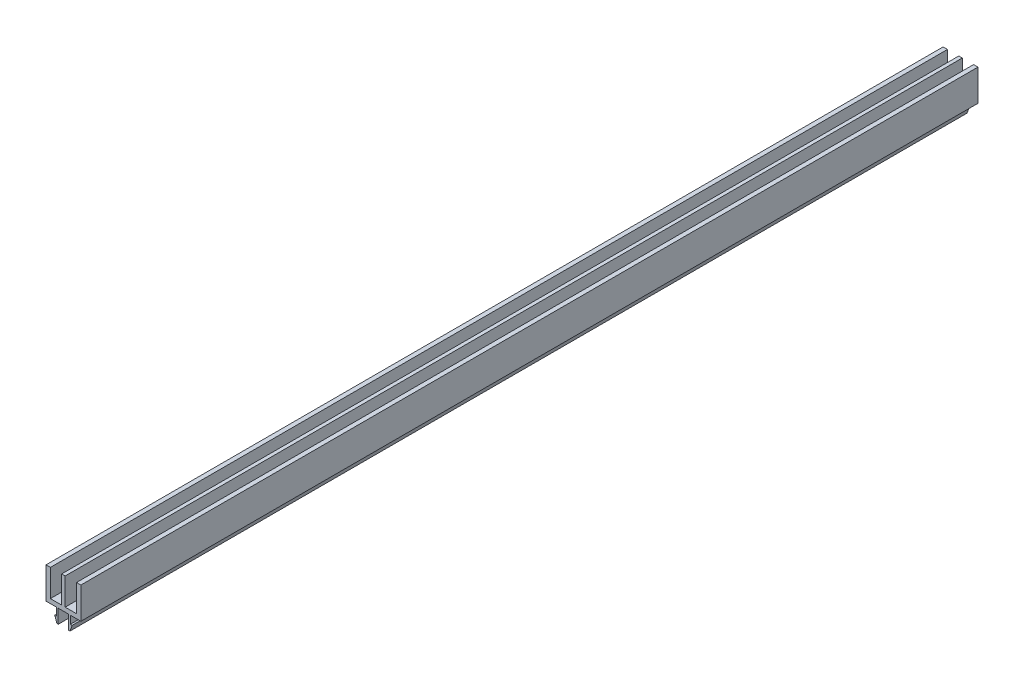
SolidWorks part; units mm, degrees
ref_plane "Plan de face" through (0, 0, 0) normal (0, 0, 1) x (1, 0, 0)
ref_plane "Plan de dessus" through (0, 0, 0) normal (0, 1, 0) x (1, 0, 0)
ref_plane "Plan de droite" through (0, 0, 0) normal (1, 0, 0) x (0, 0, -1)
ref_plane "Plan1" through (0, 0, 50) normal (0, 0, 1) x (1, 0, 0)
sketch "Esquisse1" plane through (0, 0, 50) normal (0, 0, 1) x (1, 0, 0)
  line L0 (-1, 2.5) -> (-7.5, 2.5)
  line L1 (-7.5, 2.5) -> (-7.5, 18)
  line L2 (-7.5, 18) -> (-10, 18)
  line L3 (-10, 18) -> (-10, 0)
  line L4 (-10, 0) -> (-4, 0)
  line L5 (-4, 0) -> (-4, -4.5)
  line L6 (-4, -4.5) -> (-5, -4.5)
  line L7 (-5, -4.5) -> (-3.75, -8)
  line L8 (-3.75, -8) -> (-3, -8)
  line L9 (-3, -8) -> (-3, 0)
  line L10 (-3, 0) -> (3, 0)
  line L11 (3, 0) -> (3, -8)
  line L12 (3, -8) -> (3.75, -8)
  line L13 (3.75, -8) -> (5, -4.5)
  line L14 (5, -4.5) -> (4, -4.5)
  line L15 (4, -4.5) -> (4, 0)
  line L16 (4, 0) -> (10, 0)
  line L17 (10, 0) -> (10, 18)
  line L18 (10, 18) -> (7.5, 18)
  line L19 (7.5, 18) -> (7.5, 2.5)
  line L20 (7.5, 2.5) -> (1, 2.5)
  line L21 (1, 2.5) -> (1, 18)
  line L22 (1, 18) -> (-1, 18)
  line L23 (-1, 18) -> (-1, 2.5)
extrude "Boss.-Extru.1" add sketch "Esquisse1" against normal blind 514
